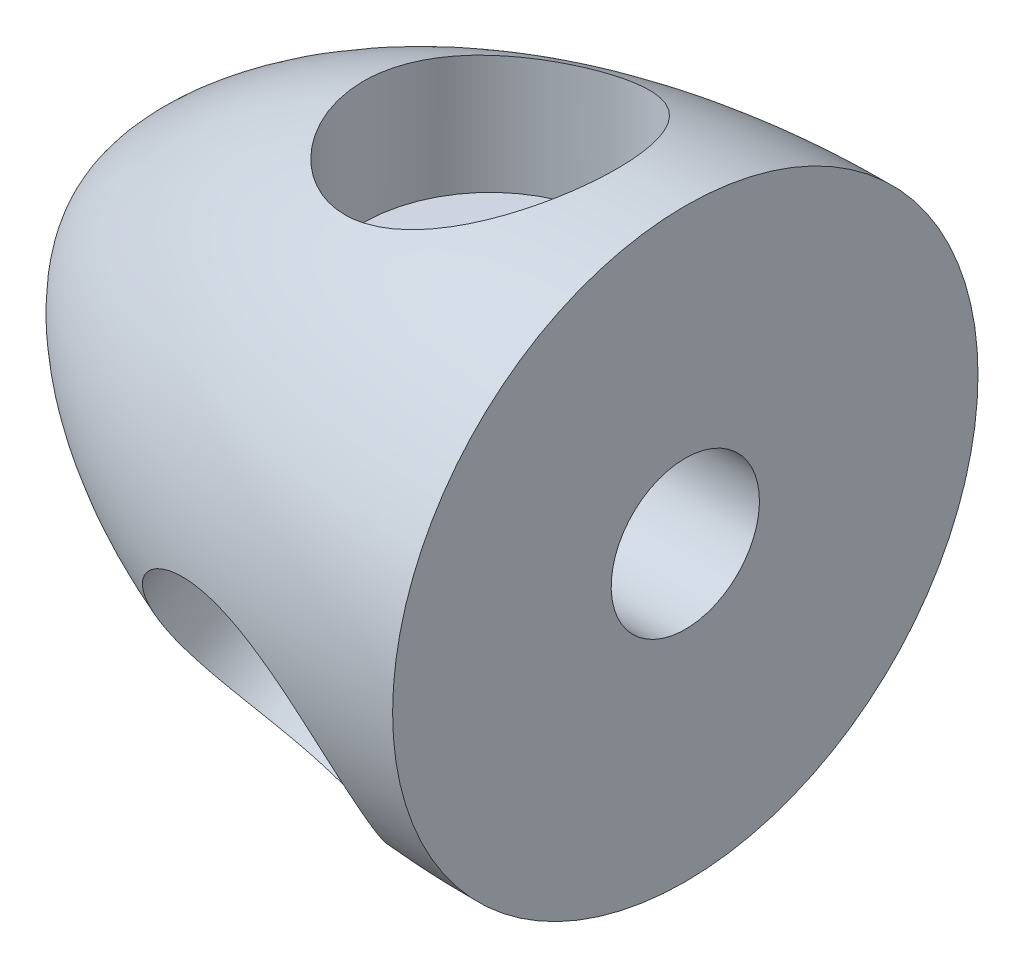
SolidWorks part; units mm, degrees
ref_plane "Front Plane" through (0, 0, 0) normal (0, 0, 1) x (1, 0, 0)
ref_plane "Top Plane" through (0, 0, 0) normal (0, 1, 0) x (1, 0, 0)
ref_plane "Right Plane" through (0, 0, 0) normal (1, 0, 0) x (0, 0, -1)
sketch "Sketch4" plane through (0, 0, 0) normal (0, 0, 1) x (1, 0, 0)
  line L0 (0, 0) -> (-38.1, 0)
  line L1 (0, 0) -> (0, 19.05)
  line L2 (-20.3467, 19.05) -> (20.3467, 19.05) construction
  line L3 (-38.1, -5.04) -> (-38.1, 5.04) construction
  spline S0 degree 3 poles (0, 19.05) (-25.4333, 19.05) (-38.1, 6.3) (-38.1, 0) knots 0 0 0 0 1 1 1 1
  point P4 (0, 0)
  dimension "D1" = 18.9
  dimension "D2" = 76.3
  dimension "D3" = 38.1
  dimension "D4" = 19.05
revolve "Revolve1" add sketch "Sketch4" angle 360 about L0
ref_plane "Plane1" through (0, 19.05, 0) normal (0, 1, 0) x (1, 0, 0)
sketch "Sketch5" plane through (0, 19.05, 0) normal (0, 1, 0) x (1, 0, 0)
  circle A0 centre (-12.7, 0) radius 8.255
  dimension "D2" = 16.51
  dimension "D1" = 12.7
extrude "Cut-Extrude1" cut sketch "Sketch5" against normal blind 11.43
pattern_circular "CirPattern1" count 3 over 360 about axis through (0, 0, 0) along (1, 0, 0) of "Cut-Extrude1"
sketch "Sketch6" plane through (0, 0, 0) normal (1, 0, 0) x (0, 0, -1)
  circle A0 centre (0, 0) radius 4.825
  dimension "D1" = 9.65
extrude "Cut-Extrude2" cut sketch "Sketch6" against normal blind 12.7
